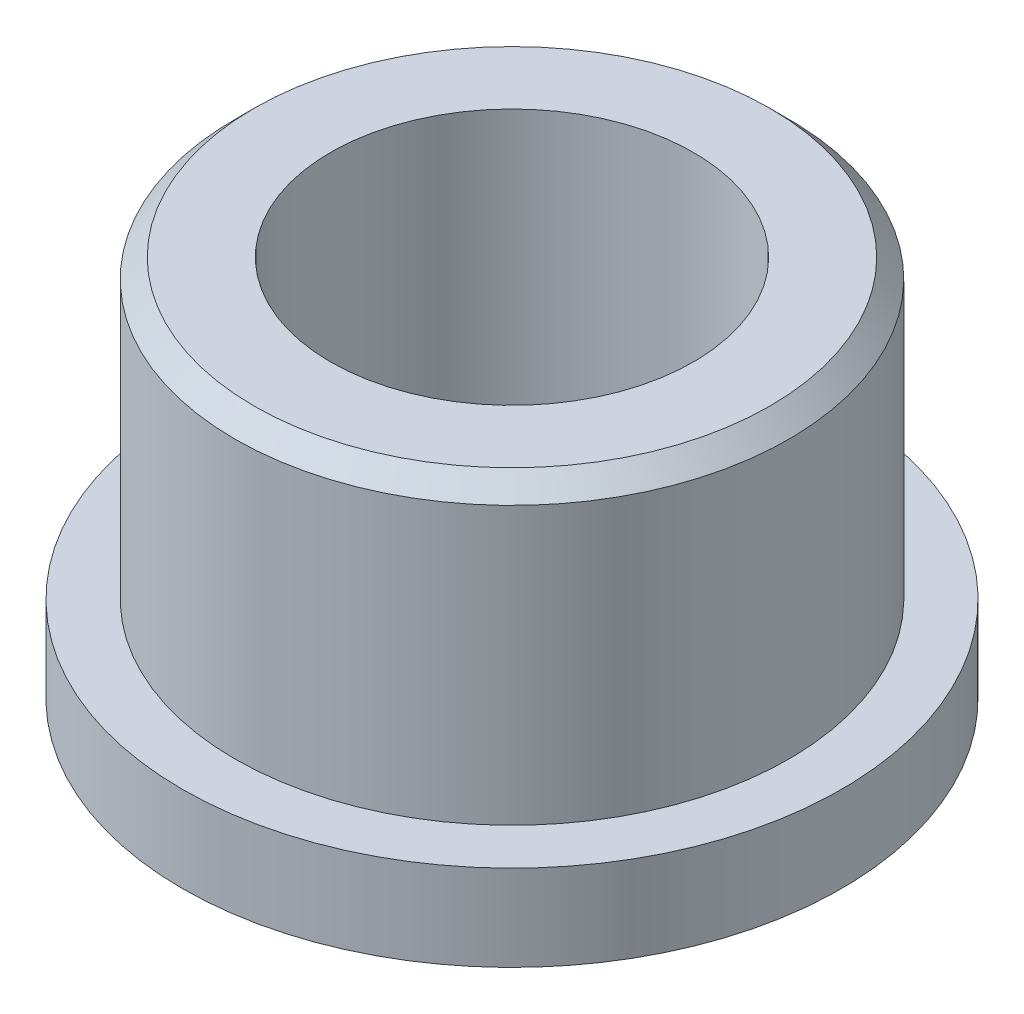
SolidWorks part; units mm, degrees
material "Polyethylene Cross-Linked"
ref_plane "Front Plane" through (0, 0, 0) normal (0, 0, 1) x (1, 0, 0)
ref_plane "Top Plane" through (0, 0, 0) normal (0, 1, 0) x (1, 0, 0)
ref_plane "Right Plane" through (0, 0, 0) normal (1, 0, 0) x (0, 0, -1)
sketch "Sketch1" plane through (0, 0, 0) normal (0, 1, 0) x (1, 0, 0)
  circle A0 centre (0, 0) radius 17.25
  circle A1 centre (0, 0) radius 9.5
  dimension "D1" = 19
  dimension "D2" = 34.5
extrude "Boss-Extrude1" add sketch "Sketch1" along normal blind 20
sketch "Sketch2" plane through (0, 20, 0) normal (0, 1, 0) x (1, 0, 0)
  circle A0 centre (0, 0) radius 14.5
  circle A1 centre (0, 0) radius 17.25
  dimension "D1" = 29
extrude "Cut-Extrude1" cut sketch "Sketch2" against normal offset from surface (15.5 mm away) 4.5 up to face at (0, 0, 17.25)
chamfer "Chamfer1" distance 1 angle 45 1 edges at (0, 20, 14.5)
